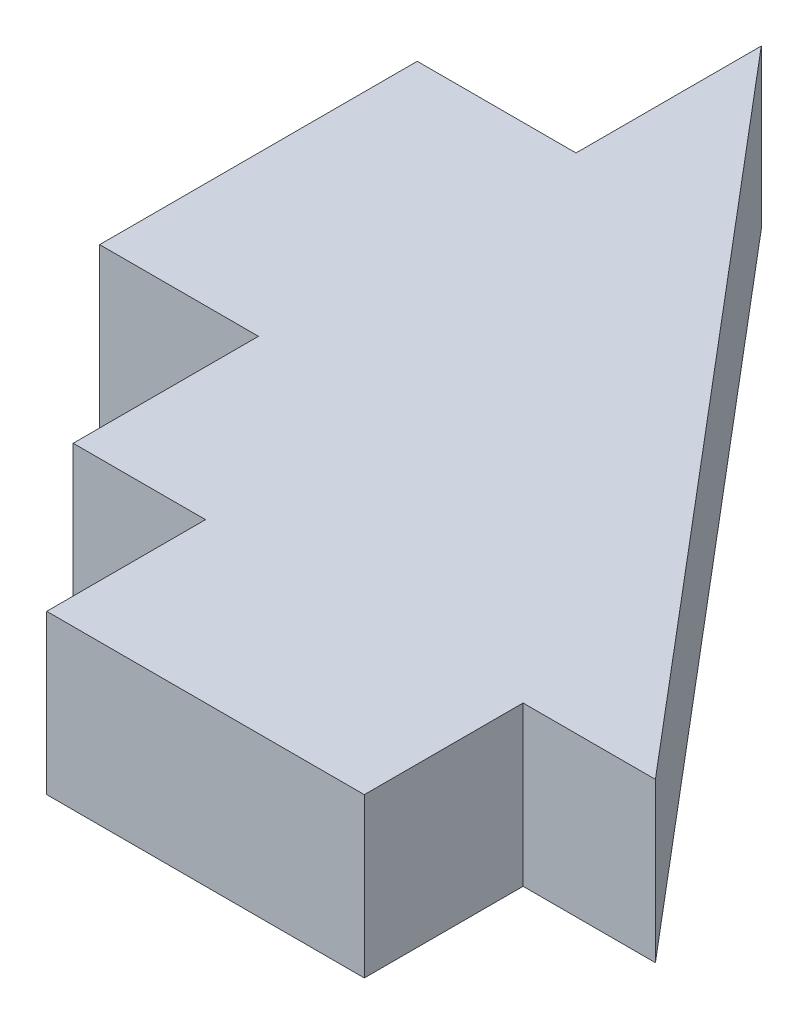
SolidWorks part; units mm, degrees
ref_plane "Alzado" through (0, 0, 0) normal (0, 0, 1) x (1, 0, 0)
ref_plane "Planta" through (0, 0, 0) normal (0, 1, 0) x (1, 0, 0)
ref_plane "Vista lateral" through (0, 0, 0) normal (1, 0, 0) x (0, 0, -1)
sketch "Croquis1" plane through (0, 0, 0) normal (0, 1, 0) x (1, 0, 0)
  line L0 (0, 0) -> (2.5, 0)
  line L1 (0, 0) -> (0, 3.5)
  line L2 (0, 13) -> (11, 0)
  line L3 (0, 9.5) -> (0, 13)
  line L4 (-3, 3.5) -> (-3, 9.5)
  line L5 (-3, 9.5) -> (0, 9.5)
  line L6 (-3, 3.5) -> (0, 3.5)
  line L7 (8.5, 0) -> (11, 0)
  line L8 (5.5, -3) -> (2.5, -3)
  line L9 (5.5, -3) -> (8.5, -3)
  line L10 (2.5, -3) -> (2.5, 0)
  line L11 (8.5, -3) -> (8.5, 0)
  dimension "D1" = 11
  dimension "D2" = 13
  dimension "D6" = 3
  dimension "D7" = 3
extrude "Saliente-Extruir1" add sketch "Croquis1" along normal blind 3
